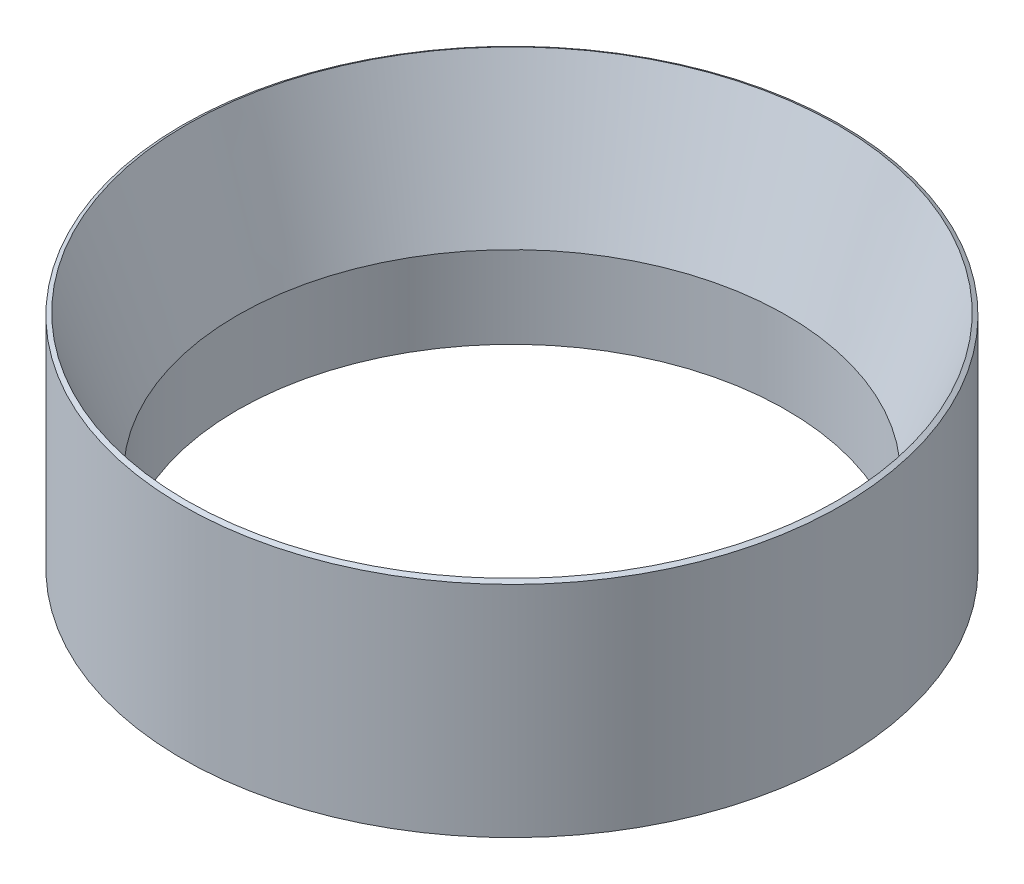
SolidWorks part; units mm, degrees
ref_plane "Front Plane" through (0, 0, 0) normal (0, 0, 1) x (1, 0, 0)
ref_plane "Top Plane" through (0, 0, 0) normal (0, 1, 0) x (1, 0, 0)
ref_plane "Right Plane" through (0, 0, 0) normal (1, 0, 0) x (0, 0, -1)
sketch "Sketch1" plane through (0, 0, 0) normal (0, 0, 1) x (1, 0, 0)
  line L0 (0, 0) -> (42.545, 0) construction
  line L3 (42.545, 12.7) -> (50.419, 34.3336)
  line L4 (51.054, 33.967) -> (51.054, 0)
  line L6 (51.054, 0) -> (42.545, 0)
  line L7 (0, 36.0783) -> (0, 0) construction
  line L8 (0, 36.0783) -> (51.054, 36.0783) construction
  line L9 (42.545, 12.7) -> (42.545, 36.0783) construction
  line L10 (50.419, 34.3336) -> (51.054, 33.967)
  line L11 (50.419, 34.3336) -> (51.054, 36.0783) construction
  line L12 (51.054, 36.0783) -> (51.054, 33.967) construction
  line L13 (42.545, 12.7) -> (42.545, 0)
  line L19 (42.545, 12.7) -> (42.545, 10.16) construction
  point P3 (51.1302, 0.2794)
  point P8 (0, 0)
  point P10 (51.054, 34.6826)
  point P11 (51.054, 34.6826)
  dimension "D1" = 60
  dimension "D2" = 42.545
  dimension "D3" = 20
  dimension "D4" = 51.054
  dimension "D6" = 12.7
  dimension "D7" = 2.54
  dimension "0.25" = 0.635
revolve "Revolve1" add sketch "Sketch1" angle 360 about L7
